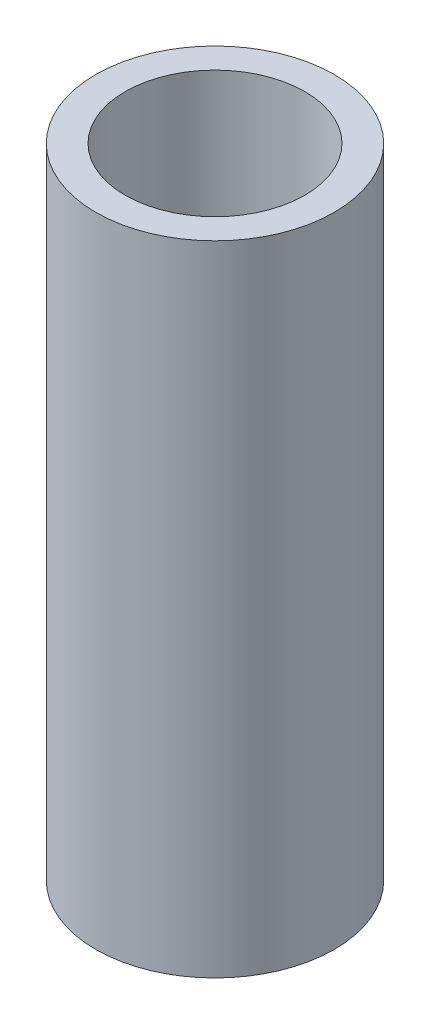
SolidWorks part; units mm, degrees
ref_plane "Front Plane" through (0, 0, 0) normal (0, 0, 1) x (1, 0, 0)
ref_plane "Top Plane" through (0, 0, 0) normal (0, 1, 0) x (1, 0, 0)
ref_plane "Right Plane" through (0, 0, 0) normal (1, 0, 0) x (0, 0, -1)
sketch "Sketch1" plane through (0, 0, 0) normal (0, 1, 0) x (1, 0, 0)
  circle A0 centre (0, 0) radius 2.65
  circle A1 centre (0, 0) radius 1.995
  dimension "D1" = 3.99
  dimension "D2" = 5.3
extrude "Boss-Extrude1" add sketch "Sketch1" along normal blind 14.18
